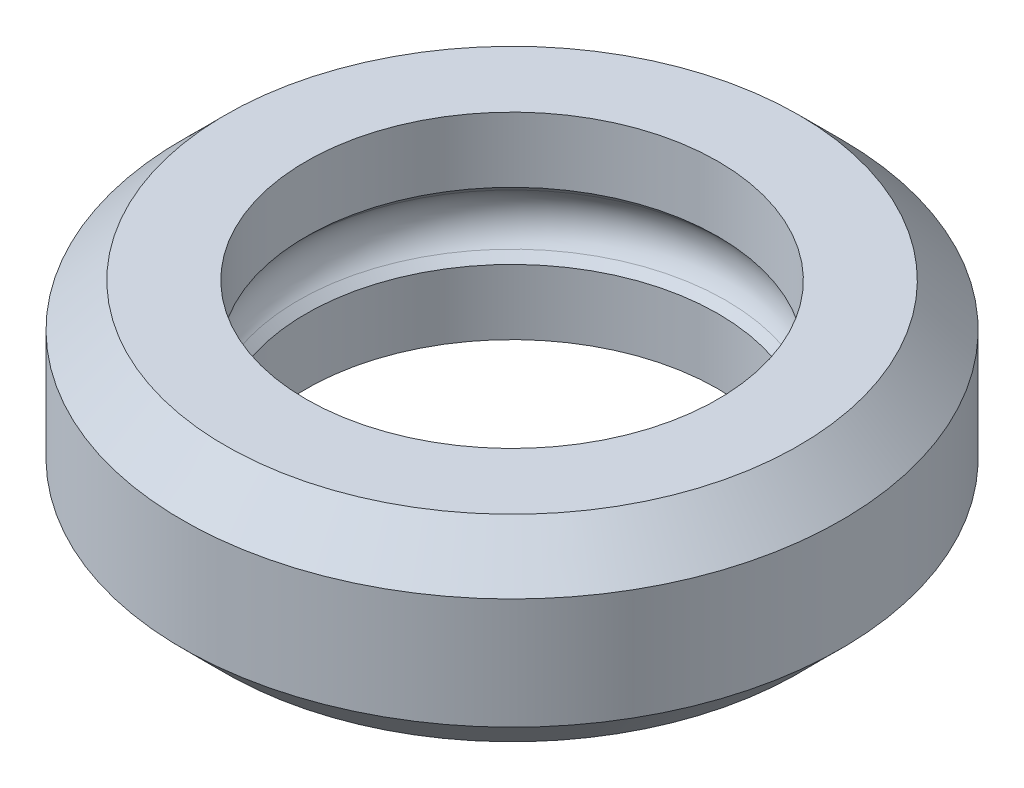
SolidWorks part; units mm, degrees
ref_plane "Front Plane" through (0, 0, 0) normal (0, 0, 1) x (1, 0, 0)
ref_plane "Top Plane" through (0, 0, 0) normal (0, 1, 0) x (1, 0, 0)
ref_plane "Right Plane" through (0, 0, 0) normal (1, 0, 0) x (0, 0, -1)
sketch "Sketch2" plane through (0, 0, 0) normal (0, 0, 1) x (1, 0, 0)
  line L0 (0, 0) -> (0, 19.8196) construction
  line L1 (0, 0) -> (10.5, 0) construction
  line L2 (9.0681, 1.4319) -> (9.5, 1.8638)
  line L3 (10.5, 0) -> (10.5, 10.5941) construction
  line L4 (9.5, 1.8638) -> (9.5, 5.5)
  line L5 (9.5, 5.5) -> (5, 5.5)
  line L6 (5, 5.5) -> (5, -5.5)
  line L7 (11.9319, 1.4319) -> (11.5, 1.8638)
  line L8 (11.5, 1.8638) -> (11.5, 5.5)
  line L9 (11.5, 5.5) -> (16, 5.5)
  line L10 (16, 5.5) -> (16, -5.5)
  line L11 (11.9319, -1.4319) -> (11.5, -1.8638)
  line L12 (9.0681, -1.4319) -> (9.5, -1.8638)
  line L13 (11.5, -5.5) -> (16, -5.5)
  line L14 (11.5, -1.8638) -> (11.5, -5.5)
  line L15 (9.5, -1.8638) -> (9.5, -5.5)
  line L16 (9.5, -5.5) -> (5, -5.5)
  line L17 (16, 0) -> (18.4, 0) construction
  line L18 (18.4, -3.1) -> (18.4, 3.1)
  line L19 (18.4, 3.1) -> (16, 5.5)
  line L20 (18.4, -3.1) -> (16, -5.5)
  line L21 (18.4, 3.1) -> (18.4, 10) construction
  line L26 (5, 5.5) -> (2.5, 5.5)
  line L27 (5, 5.5) -> (5, -5.5)
  line L28 (5, -5.5) -> (2.5, -5.5)
  line L29 (2.5, 5.5) -> (2.5, -5.5)
  arc A0 (9.0681, -1.4319) -> (9.0681, 1.4319) centre (10.5, 0) cw
  circle A1 centre (10.5, 0) radius 2 construction
  arc A2 (11.9319, -1.4319) -> (11.9319, 1.4319) centre (10.5, 0) ccw
  point P22 (16, 0)
  point P25 (5, 0)
  point P30 (18.4, 0)
  dimension "D1" = 45
  dimension "D2" = 2.025
  dimension "D3" = 4
  dimension "D4" = 2
  dimension "D5" = 6.2
  dimension "D6" = 45
  dimension "D7" = 11
  dimension "D8" = 5
  dimension "D9" = 10.5
  dimension "D10" = 2.5
  dimension "D11" = 18.4
  dimension "D12" = 6.9
  dimension "D13" = 15.5
sketch "Sketch3" plane through (0, 0, 0) normal (0, 0, 1) x (1, 0, 0)
  line L1 (10, -5) -> (11, -5)
  line L2 (10, -5) -> (10, 5)
  line L3 (10, 5) -> (11, 5)
  line L4 (11, -5) -> (11, 5)
  line L5 (10, -5) -> (11, 5) construction
  line L6 (10, 5) -> (11, -5) construction
  line L7 (0, 0) -> (0, 7.9473) construction
  line L8 (0, 0) -> (0, 19.8196) construction
  point P0 (10.5, 0)
  dimension "D1" = 1
  dimension "D2" = 10
sketch "Sketch4" plane through (0, 0, 0) normal (0, 0, 1) x (1, 0, 0)
  line L0 (10, -5) -> (11, 5) construction
  line L3 (10.5, -2.025) -> (10.5, 2.025)
  circle A1 centre (10.5, 0) radius 2.025
  point P4 (10.5, 0)
  point P9 (10.5, 0)
  dimension "D1" = 4.05
revolve "Revolve2" add sketch "Sketch2" angle 360 about L0
